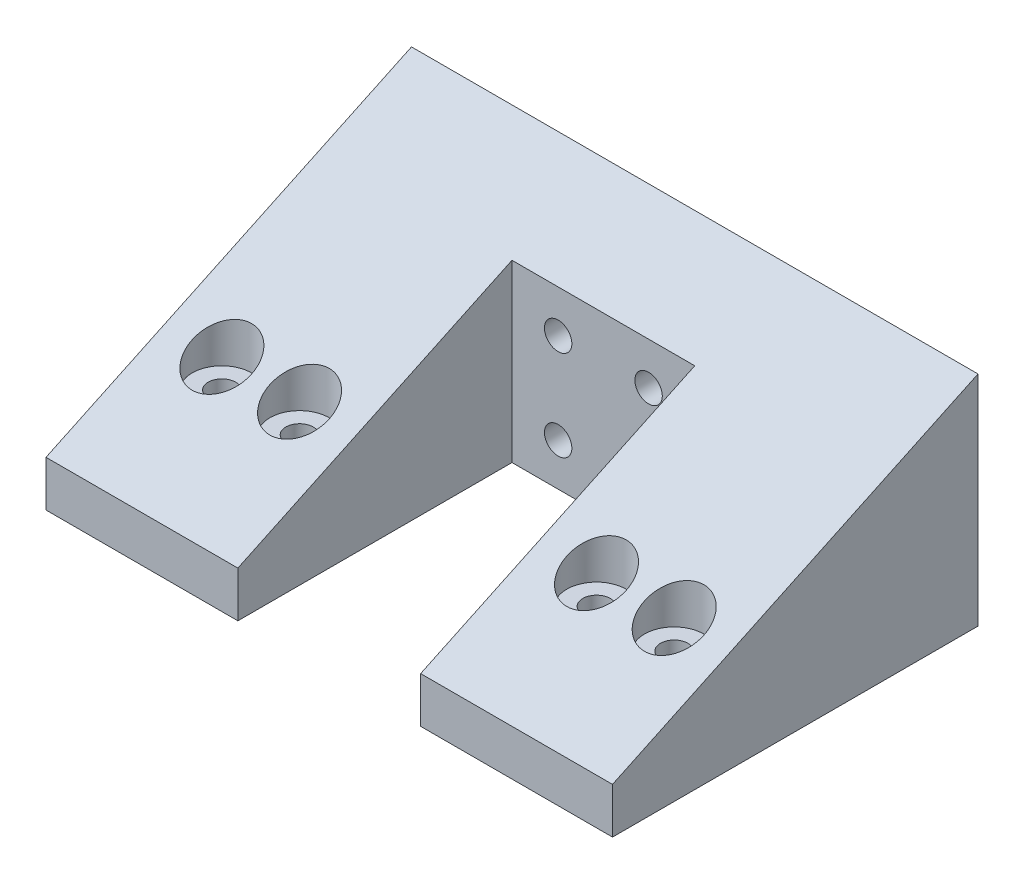
SolidWorks part; units mm, degrees
ref_plane "Спереди" through (0, 0, 0) normal (0, 0, 1) x (1, 0, 0)
ref_plane "Сверху" through (0, 0, 0) normal (0, 1, 0) x (1, 0, 0)
ref_plane "Справа" through (0, 0, 0) normal (1, 0, 0) x (0, 0, -1)
sketch "Sketch1" plane through (0, 0, 0) normal (0, 0, 1) x (1, 0, 0)
  line L0 (-31, 11.95) -> (31, -11.95) construction
  line L1 (-31, -11.95) -> (31, -11.95)
  line L2 (-31, -11.95) -> (-31, 11.95)
  line L3 (-31, 11.95) -> (31, 11.95)
  line L4 (31, -11.95) -> (31, 11.95)
  line L5 (-31, -11.95) -> (31, 11.95) construction
  point P4 (0, 0)
  dimension "D1" = 23.9
  dimension "D2" = 62
extrude "Extrude1" add sketch "Sketch1" along normal blind 40
sketch "Sketch2" plane through (0, 0, 40) normal (0, 0, 1) x (1, 0, 0)
  line L0 (-31, -11.95) -> (31, -11.95) construction
  line L1 (-10, 11.95) -> (10, 11.95)
  line L2 (-10, 11.95) -> (-10, -11.95)
  line L3 (-10, -11.95) -> (10, -11.95)
  line L4 (10, 11.95) -> (10, -11.95)
  line L5 (-31, 11.95) -> (-31, -11.95) construction
  point P6 (0, -11.95)
  point P7 (0, -11.95)
  dimension "D1" = 20
extrude "Extrude2" cut sketch "Sketch2" against normal offset from surface (30 mm away) 10 up to face at (0, 0, 0)
sketch "Sketch3" plane through (31, 0, 0) normal (1, 0, 0) x (0, 0, -1)
  line L0 (-40, -6.95) -> (-40, 11.95)
  line L1 (-40, -11.95) -> (-40, 11.95) construction
  line L2 (-40, 11.95) -> (0, 11.95)
  line L3 (0, 11.95) -> (-40, -6.95)
  line L4 (-40, 11.95) -> (0, 11.95) construction
  point P5 (0, 11.95)
  point P8 (-2.9004, 11.95)
  point P11 (0, 0)
  point P13 (-30, -4.4404)
  point P14 (0, 11.95)
  point P15 (-0.5894, 11.95)
  point P16 (6.7727, 11.95)
  point P17 (-30, -5.1997)
  point P19 (0, 11.95)
  dimension "D1" = 5
extrude "Extrude3" cut sketch "Sketch3" against normal through all
sketch "Sketch4" plane through (0, 0, 10) normal (0, 0, 1) x (1, 0, 0)
  line L0 (0, 7.225) -> (0, -11.95) construction
  line L1 (10, 7.225) -> (-10, 7.225) construction
  line L2 (-10, -11.95) -> (10, -11.95) construction
  line L3 (-10, -2.3625) -> (10, -2.3625) construction
  line L4 (-10, 7.225) -> (-10, -11.95) construction
  line L5 (10, -11.95) -> (10, 7.225) construction
  circle A0 centre (-4.95, 2.5875) radius 1.5
  circle A1 centre (4.95, 2.5875) radius 1.5
  circle A2 centre (4.95, -7.3125) radius 1.5
  circle A3 centre (-4.95, -7.3125) radius 1.5
  dimension "D1" = 3
  dimension "D4" = 9.9
  dimension "D5" = 9.9
  dimension "D6" = 4.95
  dimension "D7" = 4.95
  dimension "D2" = 2
  dimension "D3" = 2
extrude "Extrude4" cut sketch "Sketch4" against normal through all
ref_plane "Plane1" through (0, 11.95, 0) normal (0, 1, 0) x (1, 0, 0)
sketch "Sketch5" plane through (0, 11.95, 0) normal (0, 1, 0) x (1, 0, 0)
  line L1 (-31, -40) -> (-31, 0) construction
  line L3 (0, -10) -> (0, -39.3917) construction
  line L4 (10, -10) -> (-10, -10) construction
  line L7 (-31, -40) -> (-10, -40) construction
  circle A0 centre (-16.25, -27) radius 3.25
  circle A1 centre (-24.75, -27) radius 3.25
  circle A4 centre (24.75, -27) radius 3.25
  circle A5 centre (16.25, -27) radius 3.25
  point P2 (-18.1642, -28.154)
  point P3 (0, 0)
  point P8 (-37.25, -28.0154)
  point P9 (-37.25, -29.1834)
  point P13 (0, -39.3917)
  point P14 (-15.6765, -28.5829)
  point P17 (-37.25, -50)
  dimension "D1" = 6.5
  dimension "D3" = 8.5
  dimension "D4" = 6.25
  dimension "D5" = 13
  dimension "D2" = 2
extrude "Extrude5" cut sketch "Sketch5" against normal offset from surface (15.9 mm away) 8 up to face at (0, -11.95, 22.5)
sketch "Sketch6" plane through (0, 11.95, 0) normal (0, 1, 0) x (1, 0, 0)
  line L0 (0, -10) -> (0, -39.9098) construction
  line L1 (10, -10) -> (-10, -10) construction
  circle A0 centre (-24.75, -27) radius 1.5
  circle A1 centre (-16.25, -27) radius 1.5
  circle A2 centre (16.25, -27) radius 1.5
  circle A3 centre (24.75, -27) radius 1.5
  dimension "D1" = 3
extrude "Extrude6" cut sketch "Sketch6" against normal through all
